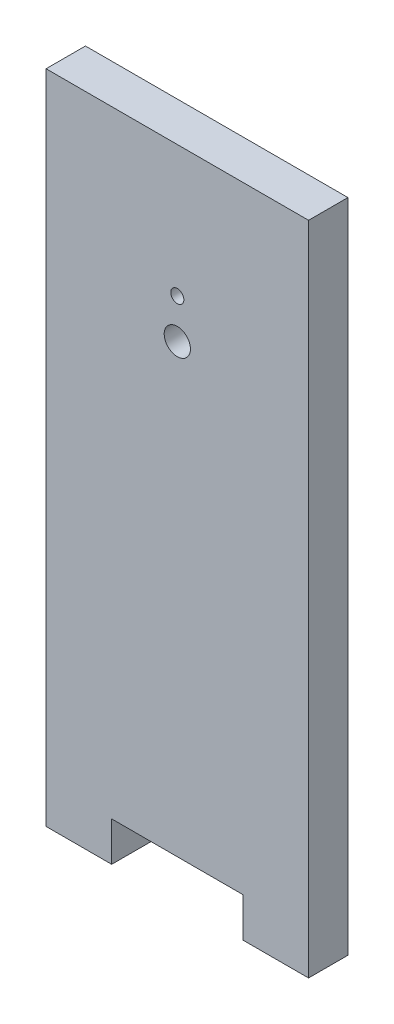
SolidWorks part; units mm, degrees
ref_plane "Front Plane" through (0, 0, 0) normal (0, 0, 1) x (1, 0, 0)
ref_plane "Top Plane" through (0, 0, 0) normal (0, 1, 0) x (1, 0, 0)
ref_plane "Right Plane" through (0, 0, 0) normal (1, 0, 0) x (0, 0, -1)
sketch "Sketch1" plane through (0, 0, 0) normal (0, 0, 1) x (1, 0, 0)
  line L0 (-5, -22) -> (5, -22)
  line L1 (5, -22) -> (5, -25)
  line L2 (10, -25) -> (5, -25)
  line L3 (10, -25) -> (10, 25)
  line L4 (10, 25) -> (-10, 25)
  line L5 (-10, -25) -> (-10, 25)
  line L6 (10, -25) -> (-10, 25) construction
  line L7 (10, 25) -> (-10, -25) construction
  line L8 (-5, -22) -> (-5, -25)
  line L9 (-5, -25) -> (-10, -25)
  circle A0 centre (0, 15) radius 0.5
  circle A1 centre (0, 12) radius 1
  point P1 (0, 0)
  dimension "D3" = 1
  dimension "D4" = 2
  dimension "D1" = 20
  dimension "D2" = 50
  dimension "D5" = 3
  dimension "D6" = 10
  dimension "D7" = 5
  dimension "D8" = 10
  dimension "3" = 3
extrude "Boss-Extrude1" add sketch "Sketch1" along normal blind 3
